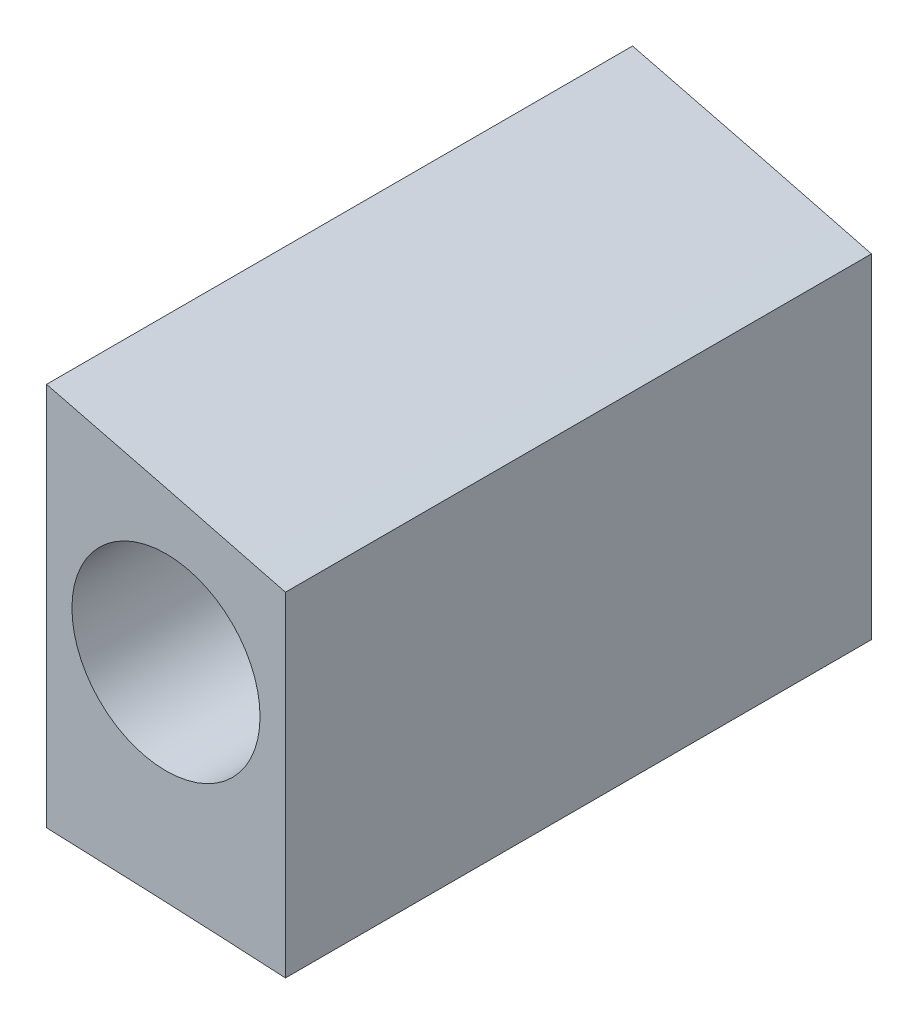
SolidWorks part; units mm, degrees
ref_plane "Front Plane" through (0, 0, 0) normal (0, 0, 1) x (1, 0, 0)
ref_plane "Top Plane" through (0, 0, 0) normal (0, 1, 0) x (1, 0, 0)
ref_plane "Right Plane" through (0, 0, 0) normal (1, 0, 0) x (0, 0, -1)
sketch "Sketch1" plane through (0, 0, 0) normal (0, 0, 1) x (1, 0, 0)
  spline S0 degree 3 poles (0.0006, 0.0001) (0.8106, 7.3592) (8.6491, 17.8566) (26.2867, 29.9752) (52.1111, 42.0692) (89.5976, 49.2908) (131.4008, 47.8848) (173.2567, 40.0411) (217.9611, 29.613) (256.9521, 19.5289) (290.3598, 8.711) (301.2732, 4.3828) (314.8169, -0.5162) (309.8463, 0.0001) knots 0 0 0 0 0.060864 0.113688 0.188609 0.312909 0.448482 0.557612 0.691544 0.852438 0.929756 0.976058 1 1 1 1
  spline S1 degree 3 poles (309.8463, 0.0001) (303.9568, 1.471) (293.9895, 2.094) (276.264, 4.5144) (260.8463, 5.4274) (235.8588, 7.8703) (205.1014, 8.8381) (157.7186, 9.0307) (110.4973, 6.1815) (66.5062, -0.5867) (36.4547, -6.0985) (15.3166, -6.1891) (1.2307, -6.9241) (0.0006, 0.0001) knots 0 0 0 0 0.057787 0.095275 0.171021 0.205339 0.335319 0.464904 0.658702 0.785512 0.893517 0.943092 1 1 1 1
extrude "Boss-Extrude1" add sketch "Sketch1" along normal blind 31.1531
sketch "Sketch2" plane through (0, 0, 31.1531) normal (0, 0, 1) x (1, 0, 0)
  circle A0 centre (20.32, 10.16) radius 6.35
  circle A1 centre (227.2963, 19.0501) radius 5
  dimension "D2" = 12.7
  dimension "D3" = 10
  dimension "D6" = 20.32
  dimension "D1" = 82.55
  dimension "D4" = 19.05
  dimension "D5" = 10.16
extrude "Cut-Extrude1" cut sketch "Sketch2" against normal through all
sketch "Sketch3" plane through (0, 0, 31.1531) normal (0, 0, 1) x (1, 0, 0)
  line L1 (350.4863, -6.3499) -> (233.6463, -6.3499)
  line L2 (350.4863, -6.3499) -> (350.4863, 44.4501)
  line L3 (350.4863, 44.4501) -> (233.6463, 44.4501)
  line L4 (233.6463, -6.3499) -> (233.6463, 44.4501)
  circle A0 centre (227.2963, 19.0501) radius 5 construction
  dimension "D1" = 6.35
  dimension "D2" = 116.84
  dimension "D3" = 50.8
  dimension "D4" = 44.45
extrude "Cut-Extrude2" cut sketch "Sketch3" against normal through all contours L3 L4 L1 L2
sketch "Sketch4" plane through (0, 0, 31.1531) normal (0, 0, 1) x (1, 0, 0)
  line L0 (233.6463, 7.6905) -> (233.6463, 25.4528) construction
  line L1 (220.9463, -24.2166) -> (-29.2042, -24.2166)
  line L2 (220.9463, -24.2166) -> (220.9463, 93.2727)
  line L3 (220.9463, 93.2727) -> (-29.2042, 93.2727)
  line L4 (-29.2042, -24.2166) -> (-29.2042, 93.2727)
  dimension "D1" = 12.7
extrude "Cut-Extrude3" cut sketch "Sketch4" against normal through all
